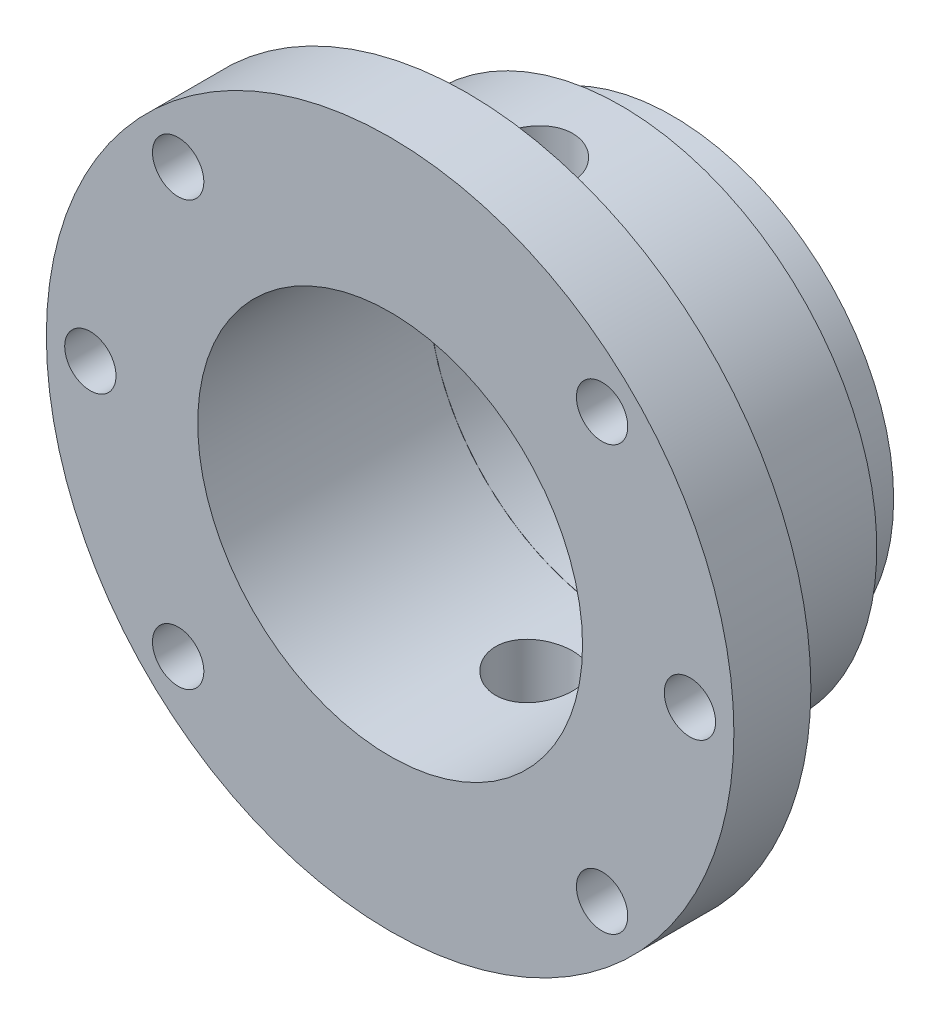
SolidWorks part; units mm, degrees
ref_plane "Спереди" through (0, 0, 0) normal (0, 0, 1) x (1, 0, 0)
ref_plane "Сверху" through (0, 0, 0) normal (0, 1, 0) x (1, 0, 0)
ref_plane "Справа" through (0, 0, 0) normal (1, 0, 0) x (0, 0, -1)
sketch "Эскиз1" plane through (0, 0, 0) normal (0, 0, 1) x (1, 0, 0)
  circle A0 centre (0, 0) radius 15
  circle A1 centre (0, 0) radius 26.8
extrude "Вытянуть1" add sketch "Эскиз1" along normal blind 18
sketch "Эскиз2" plane through (0, 0, 0) normal (0, 0, -1) x (-1, 0, 0)
  circle A0 centre (0, 0) radius 14.9815
  circle A1 centre (0, 0) radius 17.253
extrude "Вытянуть2" add sketch "Эскиз2" along normal blind 4
sketch "Эскиз3" plane through (0, 0, 0) normal (0, 0, -1) x (-1, 0, 0)
  circle A0 centre (0, 0) radius 26.8
  circle A1 centre (0, 0) radius 19.94
extrude "Вытянуть3" cut sketch "Эскиз3" against normal blind 12
sketch "Эскиз5" plane through (0, 0, 12) normal (0, 0, -1) x (-1, 0, 0)
  line L0 (-26.8, 0) -> (-26.8, 18.2105) construction
  circle A0 centre (-23.37, 0) radius 2
  circle A1 centre (-16.5251, 16.5251) radius 2
  circle A3 centre (16.5251, 16.5251) radius 2
  circle A4 centre (23.37, 0) radius 2
  circle A5 centre (16.5251, -16.5251) radius 2
  circle A7 centre (-16.5251, -16.5251) radius 2
  circle A10 centre (-23.37, 0) radius 2 [skipped]
  circle A11 centre (-16.5251, 16.5251) radius 2 [skipped]
  circle A12 centre (0, -23.37) radius 2 [skipped]
  circle A13 centre (0, 23.37) radius 2 [skipped]
  dimension "D1" = 3.43
extrude "Вытянуть4" cut sketch "Эскиз5" against normal through all
sketch "Эскиз6" plane through (0, 0, 12) normal (0, 0, -1) x (-1, 0, 0)
  line L0 (0, 29.0501) -> (0, -2.8906) construction
ref_plane "Плоскость1" through (0, 29.0501, 12) normal (0, -1, 0) x (1, 0, 0)
sketch "Эскиз7" plane through (0, 29.0501, 12) normal (0, -1, 0) x (1, 0, 0)
  circle A0 centre (0, -5.2335) radius 3
extrude "Вытянуть8" cut sketch "Эскиз7" along normal blind 100
